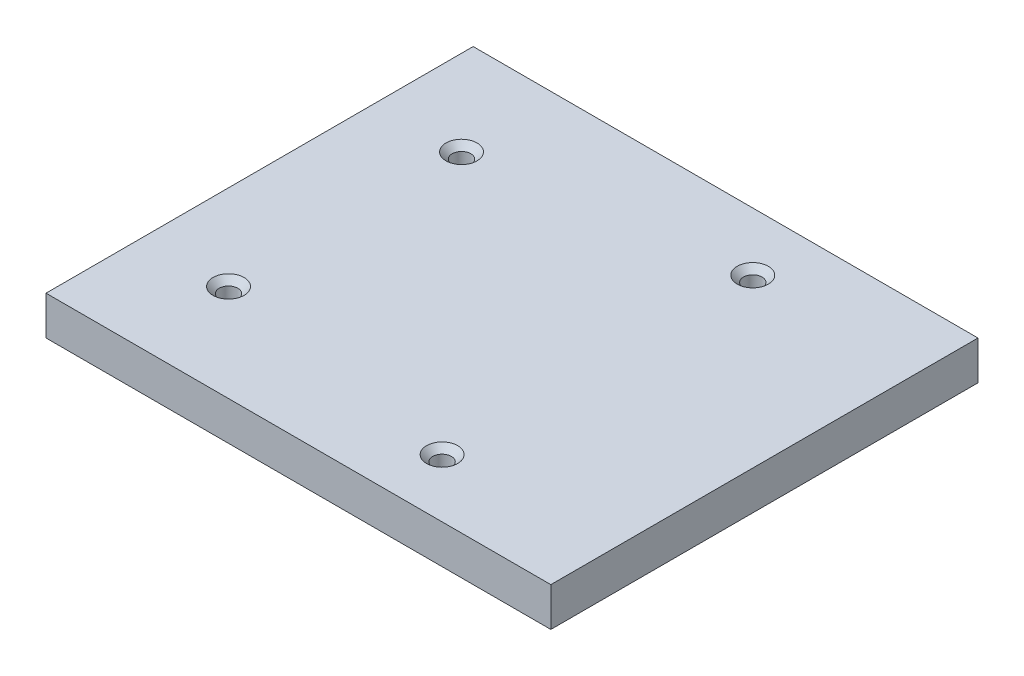
SolidWorks part; units mm, degrees
material "Сталь 08пс ГОСТ 535-88"
ref_plane "Спереди" through (0, 0, 0) normal (0, 0, 1) x (1, 0, 0)
ref_plane "Сверху" through (0, 0, 0) normal (0, 1, 0) x (1, 0, 0)
ref_plane "Справа" through (0, 0, 0) normal (1, 0, 0) x (0, 0, -1)
sketch "Эскиз1" plane through (0, 0, 0) normal (0, 0, 1) x (1, 0, 0)
  line L0 (-34.4035, 28.782) -> (34.4035, -28.782) construction
  line L1 (-34.4035, 28.782) -> (34.4035, 28.782)
  line L2 (-34.4035, 28.782) -> (-34.4035, -28.782)
  line L3 (-34.4035, -28.782) -> (34.4035, -28.782)
  line L4 (34.4035, 28.782) -> (34.4035, -28.782)
sketch "Эскиз2" plane through (0, 0, 0) normal (0, 1, 0) x (1, 0, 0)
  line L0 (-43, 55) -> (-43, -55) construction
  line L1 (-65, -55) -> (65, -55)
  line L2 (-65, -55) -> (-65, 55)
  line L3 (-65, 55) -> (65, 55)
  line L4 (65, -55) -> (65, 55)
  line L5 (-65, -55) -> (65, 55) construction
  line L6 (-65, 55) -> (65, -55) construction
  line L7 (-77.7084, 0) -> (73.6942, 0) construction
  line L8 (22, 55) -> (22, -55) construction
  circle A0 centre (-43, 30) radius 2.4
  circle A1 centre (-43, -30) radius 2.4
  circle A2 centre (22, 40) radius 2.4
  circle A3 centre (22, -40) radius 2.4
  point P0 (0, 0)
  dimension "D4" = 4.8
  dimension "D1" = 110
  dimension "D2" = 130
  dimension "D3" = 22
  dimension "D5" = 60
  dimension "D6" = 65
  dimension "D7" = 80
extrude "Бобышка-Вытянуть1" add sketch "Эскиз2" along normal mid plane 10
chamfer "Фаска1" distance 1.6 angle 45 4 edges at (22, 5, 42.4) (-43, 5, 32.4) (22, 5, -37.6) (-43, 5, -27.6)
